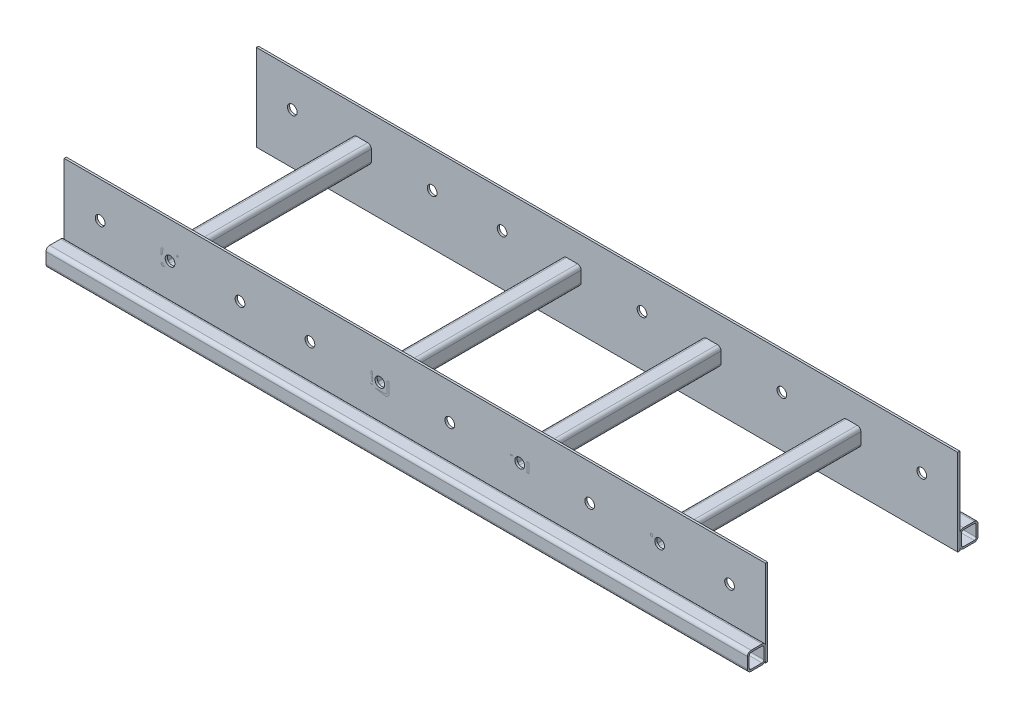
SolidWorks part; units mm, degrees
ref_plane "Front Plane" through (0, 0, 0) normal (0, 0, 1) x (1, 0, 0)
ref_plane "Top Plane" through (0, 0, 0) normal (0, 1, 0) x (1, 0, 0)
ref_plane "Right Plane" through (0, 0, 0) normal (1, 0, 0) x (0, 0, -1)
sketch "Sketch1" plane through (0, 0, 0) normal (0, 0, 1) x (1, 0, 0)
  line L1 (-437.3, 10) -> (437.3, 10) construction
  line L2 (-487.3, 60) -> (487.3, 60)
  line L3 (-487.3, -60) -> (487.3, -60)
  line L4 (-487.3, 60) -> (-487.3, -60)
  line L5 (487.3, -60) -> (487.3, 60)
  line L6 (-487.3, 0) -> (487.3, 0) construction
  circle A0 centre (-437.3, 10) radius 6.75
  circle A1 centre (-340.1222, 10) radius 6.75
  circle A2 centre (-242.9444, 10) radius 6.75
  circle A3 centre (-145.7667, 10) radius 6.75
  circle A4 centre (-48.5889, 10) radius 6.75
  circle A5 centre (48.5889, 10) radius 6.75
  circle A6 centre (145.7667, 10) radius 6.75
  circle A7 centre (242.9444, 10) radius 6.75
  circle A8 centre (340.1222, 10) radius 6.75
  circle A9 centre (437.3, 10) radius 6.75
  point P0 (240.3278, 0)
  dimension "D1" = 13.5
  dimension "D3" = 50
  dimension "D4" = 50
  dimension "D5" = 120
  dimension "D6" = 974.6
  dimension "D7" = 10
  dimension "D2" = 10
extrude "Boss-Extrude1" add sketch "Sketch1" along normal blind 3
ref_plane "Plane1" through (0, 0, 270) normal (0, 0, 1) x (1, 0, 0)
sketch "Sketch3" plane through (0, 0, 270) normal (0, 0, 1) x (1, 0, 0)
  line L0 (487.3, -60) -> (487.3, 60) construction
  line L1 (-487.3, -60) -> (487.3, -60) construction
  line L2 (-487.3, 60) -> (-487.3, -60) construction
  line L3 (487.3, 60) -> (-487.3, 60) construction
  line L4 (487.3, -60) -> (487.3, 60)
  line L5 (-487.3, -60) -> (487.3, -60)
  line L6 (-487.3, 60) -> (-487.3, -60)
  line L7 (487.3, 60) -> (-487.3, 60)
  circle A0 centre (437.3, 10) radius 6.75 construction
  circle A1 centre (340.1222, 10) radius 6.75 construction
  circle A2 centre (242.9444, 10) radius 6.75 construction
  circle A3 centre (145.7667, 10) radius 6.75 construction
  circle A4 centre (48.5889, 10) radius 6.75 construction
  circle A5 centre (-48.5889, 10) radius 6.75 construction
  circle A6 centre (-145.7667, 10) radius 6.75 construction
  circle A7 centre (-242.9444, 10) radius 6.75 construction
  circle A8 centre (-340.1222, 10) radius 6.75 construction
  circle A9 centre (-437.3, 10) radius 6.75 construction
  circle A10 centre (437.3, 10) radius 6.75
  circle A11 centre (340.1222, 10) radius 6.75
  circle A12 centre (242.9444, 10) radius 6.75
  circle A13 centre (145.7667, 10) radius 6.75
  circle A14 centre (48.5889, 10) radius 6.75
  circle A15 centre (-48.5889, 10) radius 6.75
  circle A16 centre (-145.7667, 10) radius 6.75
  circle A17 centre (-242.9444, 10) radius 6.75
  circle A18 centre (-340.1222, 10) radius 6.75
  circle A19 centre (-437.3, 10) radius 6.75
extrude "Boss-Extrude2" add sketch "Sketch3" against normal blind 3 separate body
sketch "Sketch4" plane through (0, -60, 0) normal (0, -1, 0) x (1, 0, 0)
  line L0 (-487.3, 0) -> (487.3, 0) construction
  line L1 (-487.3, 270) -> (487.3, 270) construction
  line L2 (-487.3, 0) -> (487.3, 0)
  line L3 (-487.3, 270) -> (487.3, 270)
  line L4 (-487.3, 282.5) -> (487.3, 282.5)
  line L5 (-487.3, -12.5) -> (487.3, -12.5)
  point P8 (0, 0)
  point P9 (0, 0)
  point P10 (0, 0)
  dimension "D2" = 12.5
  dimension "D4" = 12.5
other "Tube square TS25X25X2.5(1)"
ref_plane "Plane2" through (-487.3, -47.3, -12.5) normal (1, 0, 0) x (0, 0, 1)
sketch "Sketch11" plane through (-487.3, -47.3, -12.5) normal (1, 0, 0) x (0, 0, 1)
  line L0 (-7.62, -10.16) -> (7.62, -10.16)
  line L1 (-10.16, -7.62) -> (-10.16, 7.62)
  line L2 (7.62, 10.16) -> (-7.62, 10.16)
  line L3 (10.16, 7.62) -> (10.16, -7.62)
  line L4 (-7.62, -12.7) -> (7.62, -12.7)
  line L5 (-12.7, -7.62) -> (-12.7, 7.62)
  line L6 (7.62, 12.7) -> (-7.62, 12.7)
  line L7 (12.7, 7.62) -> (12.7, -7.62)
  line L8 (-12.7, 0) -> (-10.16, 0) construction
  line L9 (-10.16, 0) -> (10.16, 0) construction
  line L10 (10.16, 0) -> (12.7, 0) construction
  line L11 (0, 12.7) -> (0, 10.16) construction
  line L12 (0, 10.16) -> (0, -10.16) construction
  line L13 (0, -10.16) -> (0, -12.7) construction
  arc A0 (12.7, 7.62) -> (7.62, 12.7) centre (7.62, 7.62) ccw
  arc A1 (7.62, -12.7) -> (12.7, -7.62) centre (7.62, -7.62) ccw
  arc A2 (-12.7, -7.62) -> (-7.62, -12.7) centre (-7.62, -7.62) ccw
  arc A3 (-7.62, 12.7) -> (-12.7, 7.62) centre (-7.62, 7.62) ccw
  arc A4 (-7.62, 10.16) -> (-10.16, 7.62) centre (-7.62, 7.62) ccw
  arc A5 (10.16, 7.62) -> (7.62, 10.16) centre (7.62, 7.62) ccw
  arc A6 (7.62, -10.16) -> (10.16, -7.62) centre (7.62, -7.62) ccw
  arc A7 (-10.16, -7.62) -> (-7.62, -10.16) centre (-7.62, -7.62) ccw
  point P6 (-12.7, 12.7)
  point P33 (12.7, 12.7)
  point P34 (-12.7, -12.7)
  point P36 (12.7, -12.7)
  point P37 (0, 0)
  point P38 (0, 0)
  dimension "D1" = 5.08
  dimension "Thickness" = 2.54
  dimension "V_leg" = 25.4
  dimension "H_leg" = 25.4
sketch3d "3DSketch1"
  line L0 (340.1222, 10, 0) -> (340.1222, 10, 270)
  line L1 (-48.5889, 10, 0) -> (-48.5889, 10, 270)
  line L2 (-340.1222, 10, 270) -> (-340.1222, 10, 0)
  line L3 (-340.1222, 10, 267) -> (-340.1222, 10, 270) construction
  line L4 (145.7667, 10, 0) -> (145.7667, 10, 270)
other "Tube square TS25X25X2.5(2)"
ref_plane "Plane3" through (340.1222, 10, 0) normal (0, 0, 1) x (1, 0, 0)
sketch "Sketch12" plane through (340.1222, 10, 0) normal (0, 0, 1) x (1, 0, 0)
  line L0 (-7.62, -10.16) -> (7.62, -10.16)
  line L1 (-10.16, -7.62) -> (-10.16, 7.62)
  line L2 (7.62, 10.16) -> (-7.62, 10.16)
  line L3 (10.16, 7.62) -> (10.16, -7.62)
  line L4 (-7.62, -12.7) -> (7.62, -12.7)
  line L5 (-12.7, -7.62) -> (-12.7, 7.62)
  line L6 (7.62, 12.7) -> (-7.62, 12.7)
  line L7 (12.7, 7.62) -> (12.7, -7.62)
  line L8 (-12.7, 0) -> (-10.16, 0) construction
  line L9 (-10.16, 0) -> (10.16, 0) construction
  line L10 (10.16, 0) -> (12.7, 0) construction
  line L11 (0, 12.7) -> (0, 10.16) construction
  line L12 (0, 10.16) -> (0, -10.16) construction
  line L13 (0, -10.16) -> (0, -12.7) construction
  arc A0 (12.7, 7.62) -> (7.62, 12.7) centre (7.62, 7.62) ccw
  arc A1 (7.62, -12.7) -> (12.7, -7.62) centre (7.62, -7.62) ccw
  arc A2 (-12.7, -7.62) -> (-7.62, -12.7) centre (-7.62, -7.62) ccw
  arc A3 (-7.62, 12.7) -> (-12.7, 7.62) centre (-7.62, 7.62) ccw
  arc A4 (-7.62, 10.16) -> (-10.16, 7.62) centre (-7.62, 7.62) ccw
  arc A5 (10.16, 7.62) -> (7.62, 10.16) centre (7.62, 7.62) ccw
  arc A6 (7.62, -10.16) -> (10.16, -7.62) centre (7.62, -7.62) ccw
  arc A7 (-10.16, -7.62) -> (-7.62, -10.16) centre (-7.62, -7.62) ccw
  point P6 (-12.7, 12.7)
  point P33 (12.7, 12.7)
  point P34 (-12.7, -12.7)
  point P36 (12.7, -12.7)
  point P37 (0, 0)
  point P38 (0, 0)
  dimension "D1" = 5.08
  dimension "Thickness" = 2.54
  dimension "V_leg" = 25.4
  dimension "H_leg" = 25.4
